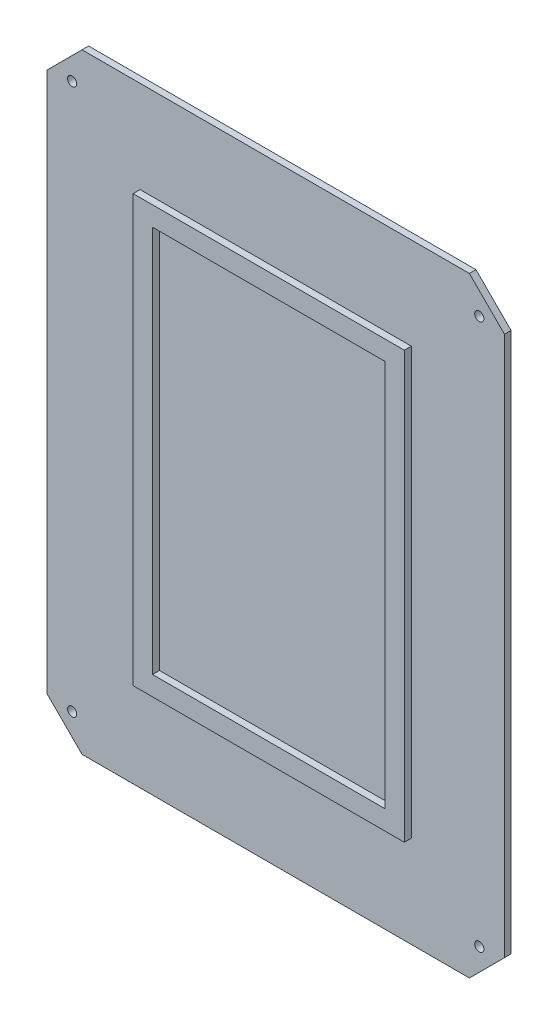
SolidWorks part; units mm, degrees
ref_plane "Front Plane" through (0, 0, 0) normal (0, 0, 1) x (1, 0, 0)
ref_plane "Top Plane" through (0, 0, 0) normal (0, 1, 0) x (1, 0, 0)
ref_plane "Right Plane" through (0, 0, 0) normal (1, 0, 0) x (0, 0, -1)
sketch "Sketch1" plane through (0, 0, 0) normal (0, 0, 1) x (1, 0, 0)
  line L0 (-149.987, 177.025) -> (-126.987, 200.025) construction
  line L1 (-149.987, -200.025) -> (149.987, -200.025)
  line L2 (-149.987, -200.025) -> (-149.987, 200.025)
  line L3 (-149.987, 200.025) -> (149.987, 200.025)
  line L4 (149.987, -200.025) -> (149.987, 200.025)
  line L5 (-149.987, -200.025) -> (149.987, 200.025) construction
  line L6 (-149.987, 200.025) -> (149.987, -200.025) construction
  line L8 (-50, -178.943) -> (50, -178.943) construction
  line L9 (-50, -178.943) -> (-50, 178.943) construction
  line L10 (-50, 178.943) -> (50, 178.943) construction
  line L11 (50, -178.943) -> (50, 178.943) construction
  line L12 (0, 178.943) -> (0, -178.943) construction
  line L13 (-50, 0) -> (50, 0) construction
  circle A0 centre (50, 178.943) radius 3
  point P0 (0, 0)
  point P8 (0, 0)
  point P13 (0, 178.943)
  point P14 (50, 181.943)
  dimension "Mounting Hole Diameter" = 6
  dimension "Height" = 400.05
  dimension "Width" = 299.974
  dimension "Chamfer Angle" = 45
  dimension "Chamfer Distance" = 23
  dimension "Mounting Hole Center to Center Height" = 357.886
  dimension "Mounting Hole Center to Center Width" = 100
  dimension "Mounting Hole Spacing" = 50
sketch "Sketch2" plane through (0, 0, 0) normal (1, 0, 0) x (0, 0, -1)
  line L0 (-2.159, 200.025) -> (2.159, 200.025) construction
  point P3 (0, 200.025)
  dimension "Thickness" = 4.318
sketch "Sketch3" plane through (0, 0, 0) normal (0, 0, 1) x (1, 0, 0)
  line L0 (-149.987, 177.025) -> (-126.987, 200.025)
  line L1 (-126.987, 200.025) -> (126.987, 200.025)
  line L2 (-149.987, 200.025) -> (149.987, 200.025) construction
  line L3 (126.987, 200.025) -> (149.987, 177.025)
  line L4 (149.987, -200.025) -> (149.987, 200.025) construction
  line L5 (149.987, 177.025) -> (149.987, -177.025)
  line L6 (149.987, -177.025) -> (126.987, -200.025)
  line L7 (-149.987, -200.025) -> (149.987, -200.025) construction
  line L8 (126.987, -200.025) -> (-126.987, -200.025)
  line L9 (-126.987, -200.025) -> (-149.987, -177.025)
  line L10 (-149.987, -200.025) -> (-149.987, 200.025) construction
  line L11 (-149.987, -177.025) -> (-149.987, 177.025)
extrude "Boss-Extrude1" add sketch "Sketch3" against normal up to vertex (2.159 mm away) and the other way up to vertex (2.159 mm away) up to point (0, 200.025, -2.159) other way up to point (0, 200.025, 2.159)
sketch "Sketch4" plane through (0, 0, 0) normal (0, 0, 1) x (1, 0, 0)
  line L1 (53, 178.943) -> (53, 200.025)
  line L3 (-149.987, 200.025) -> (149.987, 200.025) construction
  line L6 (53, 200.025) -> (47, 200.025)
  line L7 (47, 200.025) -> (47, 178.943)
  circle A0 centre (50, 178.943) radius 3 construction
  arc A1 (47, 178.943) -> (53, 178.943) centre (50, 178.943) ccw
sketch "Sketch6" plane through (0, 0, -2.159) normal (0, 0, -1) x (-1, 0, 0)
  line L1 (-88.9, 139.7) -> (88.9, 139.7)
  line L2 (-88.9, 139.7) -> (-88.9, -139.7)
  line L3 (-88.9, -139.7) -> (88.9, -139.7)
  line L4 (88.9, 139.7) -> (88.9, -139.7)
  line L5 (-88.9, 139.7) -> (88.9, -139.7) construction
  line L6 (-88.9, -139.7) -> (88.9, 139.7) construction
  line L7 (-76.2, 127) -> (76.2, 127)
  line L8 (-76.2, 127) -> (-76.2, -127)
  line L9 (-76.2, -127) -> (76.2, -127)
  line L10 (76.2, 127) -> (76.2, -127)
  line L11 (-76.2, 127) -> (76.2, -127) construction
  line L12 (-76.2, -127) -> (76.2, 127) construction
  point P0 (0, 0)
  point P6 (0, 0)
  dimension "D1" = 177.8
  dimension "D2" = 12.7
  dimension "D3" = 12.7
  dimension "D4" = 279.4
extrude "Boss-Extrude2" add sketch "Sketch6" against normal blind 8.89
sketch "Sketch7" plane through (0, 0, -2.159) normal (0, 0, -1) x (-1, 0, 0)
  line L9 (-133.477, -178.943) -> (133.477, -178.943) construction
  line L10 (-133.477, -178.943) -> (-133.477, 178.943) construction
  line L11 (-133.477, 178.943) -> (133.477, 178.943) construction
  line L12 (133.477, -178.943) -> (133.477, 178.943) construction
  line L13 (-133.477, -178.943) -> (133.477, 178.943) construction
  line L14 (-133.477, 178.943) -> (133.477, -178.943) construction
  circle A0 centre (133.477, 178.943) radius 3
  circle A1 centre (-133.477, 178.943) radius 3
  circle A2 centre (-133.477, -178.943) radius 3
  circle A3 centre (133.477, -178.943) radius 3
  point P8 (0, 0)
  dimension "D1" = 6
  dimension "D2" = 266.954
  dimension "D3" = 357.886
extrude "Cut-Extrude2" cut sketch "Sketch7" against normal through all
